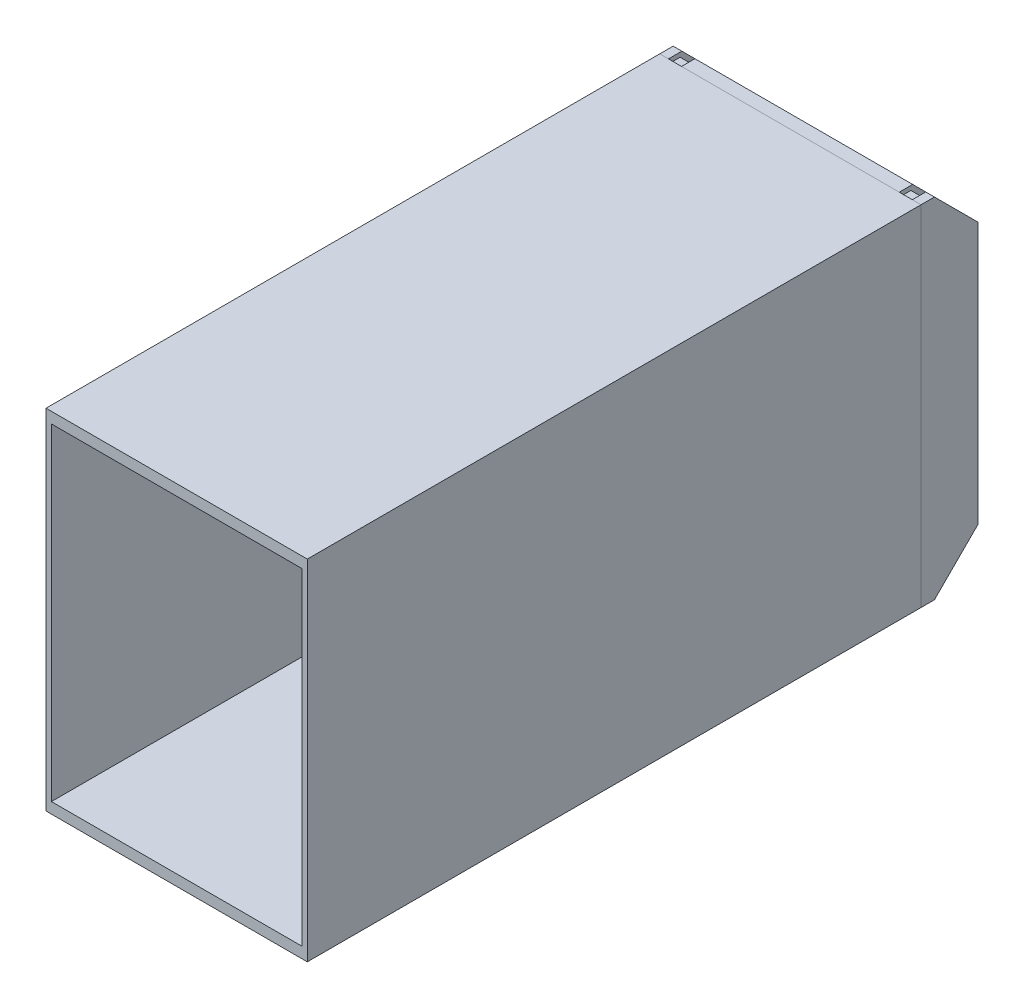
SolidWorks part; units mm, degrees
ref_plane "Front Plane" through (0, 0, 0) normal (0, 0, 1) x (1, 0, 0)
ref_plane "Top Plane" through (0, 0, 0) normal (0, 1, 0) x (1, 0, 0)
ref_plane "Right Plane" through (0, 0, 0) normal (1, 0, 0) x (0, 0, -1)
ref_plane "Plane1" through (0, 0, 0) normal (0, 0, -1) x (-1, 0, 0)
sketch "Sketch1" plane through (0, 0, 0) normal (0, 0, -1) x (-1, 0, 0)
  line L0 (300, -525) -> (300, 276)
  line L1 (300, 276) -> (-300, 276)
  line L2 (-300, 276) -> (-300, -525)
  line L3 (-300, -525) -> (300, -525)
  dimension "D1" = 600
  dimension "D2" = 801
extrude "Boss-Extrude1" add sketch "Sketch1" against normal blind 30.8
sketch "Sketch2" plane through (0, 0, 30.8) normal (0, 0, 1) x (1, 0, 0)
  line L0 (256.75, -500) -> (287.55, -500) construction
  line L1 (-300, 276) -> (300, 276)
  line L2 (-300, 276) -> (-300, -525)
  line L3 (-300, -525) -> (300, -525)
  line L4 (300, 276) -> (300, -525)
  line L5 (-287.55, 251) -> (287.55, 251)
  line L6 (-287.55, 251) -> (-287.55, -500)
  line L7 (-287.55, -500) -> (287.55, -500)
  line L8 (287.55, 251) -> (287.55, -500)
  line L9 (287.55, -400) -> (287.55, -500) construction
extrude "Boss-Extrude2" add sketch "Sketch2" along normal up to surface (1409.2 mm away)
sketch "Sketch3" plane through (0, 0, 0) normal (0, 0, -1) x (-1, 0, 0)
  line L0 (300, -525) -> (300, 276) construction
  line L1 (-300, 176) -> (300, 176)
  line L2 (-300, 176) -> (-300, -425)
  line L3 (-300, -425) -> (300, -425)
  line L4 (300, 176) -> (300, -425)
  line L5 (-300, 276) -> (-300, -525) construction
  line L6 (300, 276) -> (-300, 276) construction
  line L7 (-300, -525) -> (300, -525) construction
  dimension "D1" = 100
  dimension "D2" = 100
extrude "Boss-Extrude3" add sketch "Sketch3" along normal blind 100
ref_plane "Plane2" through (0, 138, -138) normal (0, -0.7071, 0.7071) x (1, 0, 0)
sketch "Sketch4" plane through (0, 138, -138) normal (0, -0.7071, 0.7071) x (1, 0, 0)
  line L0 (-300, 53.7401) -> (300, 53.7401) construction
  line L1 (300, 195.1615) -> (-300, 195.1615)
  line L2 (300, 195.1615) -> (300, 53.7401)
  line L3 (300, 53.7401) -> (-300, 53.7401)
  line L4 (-300, 195.1615) -> (-300, 53.7401)
extrude "Boss-Extrude4" add sketch "Sketch4" along normal blind 100
ref_plane "Plane3" through (0, -262.5, -262.5) normal (0, 0.7071, 0.7071) x (1, 0, 0)
sketch "Sketch5" plane through (0, -262.5, -262.5) normal (0, 0.7071, 0.7071) x (1, 0, 0)
  line L1 (300, -229.8097) -> (-300, -229.8097)
  line L2 (300, -229.8097) -> (300, -371.2311)
  line L3 (300, -371.2311) -> (-300, -371.2311)
  line L4 (-300, -229.8097) -> (-300, -371.2311)
extrude "Boss-Extrude5" add sketch "Sketch5" along normal blind 100
sketch "Sketch6" plane through (0, -525, 0) normal (0, -1, 0) x (1, 0, 0)
  line L0 (300, 0) -> (-300, 0) construction
  line L1 (280, 0) -> (250, 0)
  line L2 (280, 0) -> (280, 1375)
  line L4 (250, 0) -> (250, 1345)
  line L5 (300, 30.8) -> (300, 0) construction
  line L6 (300, 1440) -> (-300, 1440) construction
  line L7 (225, 1370) -> (-225, 1370)
  line L9 (255, 1400) -> (-255, 1400)
  line L12 (-300, 30.8) -> (-300, 0) construction
  line L13 (-280, 0) -> (-250, 0)
  line L14 (-280, 0) -> (-280, 1375)
  line L16 (-250, 0) -> (-250, 1345)
  arc A0 (-225, 1370) -> (-250, 1345) centre (-225, 1345) ccw
  arc A1 (-255, 1400) -> (-280, 1375) centre (-255, 1375) ccw
  arc A2 (225, 1370) -> (250, 1345) centre (225, 1345) cw
  arc A3 (280, 1375) -> (255, 1400) centre (255, 1375) ccw
  dimension "D7" = 25
  dimension "D1" = 30
  dimension "D2" = 20
  dimension "D3" = 30
  dimension "D4" = 40
  dimension "D5" = 20
  dimension "D6" = 30
extrude "Cut-Extrude1" cut sketch "Sketch6" against normal blind 10
sketch "Sketch7" plane through (0, -262.5, -262.5) normal (0, -0.7071, -0.7071) x (1, 0, 0)
  line L0 (300, 229.8097) -> (-300, 229.8097) construction
  line L1 (-280, 371.2311) -> (-250, 371.2311)
  line L2 (-280, 371.2311) -> (-280, 229.8097)
  line L3 (-280, 229.8097) -> (-250, 229.8097)
  line L4 (-250, 371.2311) -> (-250, 229.8097)
  line L5 (-250, 371.2311) -> (-250, 393.0099) construction
  line L6 (280, 371.2311) -> (280, 393.0099) construction
  line L7 (250, 371.2311) -> (280, 371.2311)
  line L8 (250, 371.2311) -> (250, 229.8097)
  line L9 (250, 229.8097) -> (280, 229.8097)
  line L10 (280, 371.2311) -> (280, 229.8097)
extrude "Cut-Extrude2" cut sketch "Sketch7" against normal blind 10
sketch "Sketch8" plane through (0, 276, 0) normal (0, 1, 0) x (1, 0, 0)
  line L0 (-280, 0) -> (-250, 0)
  line L1 (-280, 0) -> (-280, -1375)
  line L2 (-250, 0) -> (-250, -1345)
  line L3 (-225, -1370) -> (225, -1370)
  line L4 (-255, -1400) -> (255, -1400)
  line L5 (280, 0) -> (250, 0)
  line L6 (280, 0) -> (280, -1375)
  line L7 (250, 0) -> (250, -1345)
  line L10 (-300, 0) -> (300, 0) construction
  line L11 (-300, -30.8) -> (-300, 0) construction
  arc A0 (225, -1370) -> (250, -1345) centre (225, -1345) ccw
  arc A1 (255, -1400) -> (280, -1375) centre (255, -1375) ccw
  arc A2 (-225, -1370) -> (-250, -1345) centre (-225, -1345) cw
  arc A3 (-280, -1375) -> (-255, -1400) centre (-255, -1375) ccw
  dimension "D4" = 25
  dimension "D1" = 30
  dimension "D2" = 30
  dimension "D3" = 30
  dimension "D5" = 500
  dimension "D6" = 1370
  dimension "D7" = 20
extrude "Cut-Extrude3" cut sketch "Sketch8" against normal blind 10
sketch "Sketch9" plane through (0, 138, -138) normal (0, 0.7071, -0.7071) x (1, 0, 0)
  line L0 (-300, -53.7401) -> (300, -53.7401) construction
  line L1 (-250, -195.1615) -> (-280, -195.1615)
  line L2 (-250, -195.1615) -> (-250, -53.7401)
  line L3 (-250, -53.7401) -> (-280, -53.7401)
  line L4 (-280, -195.1615) -> (-280, -53.7401)
  line L5 (-280, -195.1615) -> (-280, -216.9404) construction
  line L6 (250, -195.1615) -> (250, -216.9404) construction
  line L7 (280, -195.1615) -> (250, -195.1615)
  line L8 (280, -195.1615) -> (280, -53.7401)
  line L9 (280, -53.7401) -> (250, -53.7401)
  line L10 (250, -195.1615) -> (250, -53.7401)
extrude "Cut-Extrude4" cut sketch "Sketch9" against normal blind 10
ref_plane "Plane4" through (0, 0, 0) normal (1, 0, 0) x (0, 0, -1)
sketch "Sketch12" plane through (0, 0, 0) normal (1, 0, 0) x (0, 0, -1)
  line L0 (-740, -525) -> (-340, -525)
  line L1 (-340, -525) -> (-340, -505)
  line L2 (-340, -505) -> (-740, -525)
  line L3 (-30.8, -525) -> (0, -525) construction
  line L5 (-1440, 276) -> (-1440, -525) construction
  point P7 (-340, -515)
  dimension "D1" = 1100
  dimension "D2" = 400
  dimension "D3" = 20
extrude "Cut-Extrude5" cut sketch "Sketch12" against normal blind 130 and the other way blind 130
sketch "Sketch13" plane through (0, -525, 0) normal (0, -1, 0) x (1, 0, 0)
  line L0 (37.8333, 111) -> (189.1667, 111) construction
  line L1 (475.8483, 667.9512) -> (627.1817, 667.9512) construction
sketch "Sketch14"
  line L0 (690.9299, 2674.5932) -> (3250.9299, 2674.5932) construction
  line L1 (537.659, 311.5059) -> (865.659, 311.5059) construction
  line L2 (116.3663, 704.031) -> (267.6996, 704.031) construction
